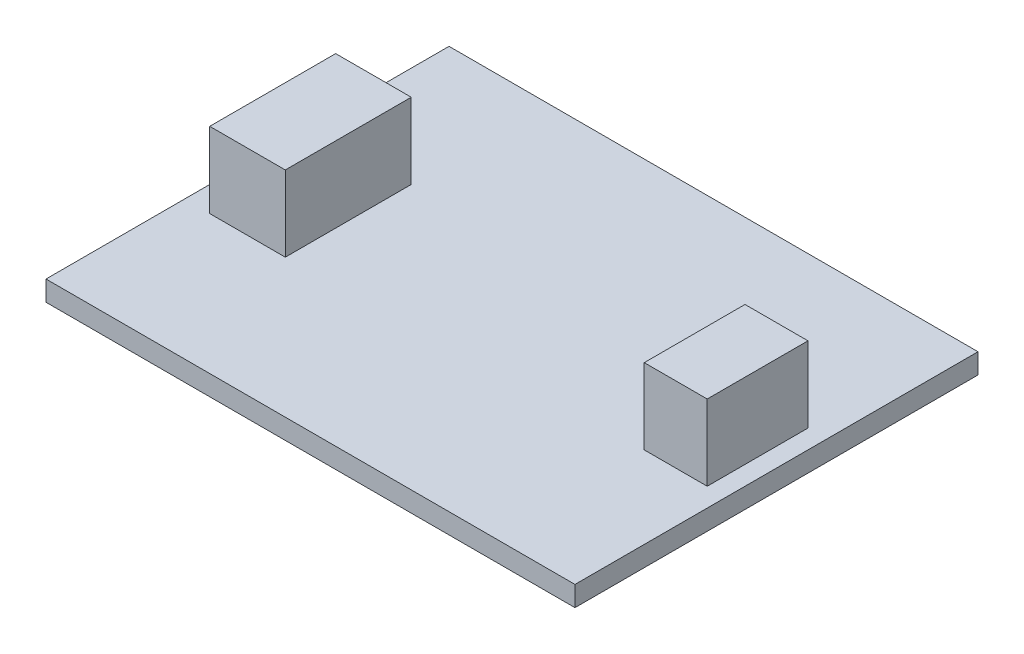
SolidWorks part; units mm, degrees
ref_plane "Front Plane" through (0, 0, 0) normal (0, 0, 1) x (1, 0, 0)
ref_plane "Top Plane" through (0, 0, 0) normal (0, 1, 0) x (1, 0, 0)
ref_plane "Right Plane" through (0, 0, 0) normal (1, 0, 0) x (0, 0, -1)
other "Configuration Table"
sketch "Sketch1" plane through (0, 0, 0) normal (0, 1, 0) x (1, 0, 0)
  line L1 (-21, -16) -> (21, -16)
  line L2 (-21, -16) -> (-21, 16)
  line L3 (-21, 16) -> (21, 16)
  line L4 (21, -16) -> (21, 16)
  line L5 (-21, -16) -> (21, 16) construction
  line L6 (-21, 16) -> (21, -16) construction
  point P6 (0, 0)
  dimension "D1" = 42
  dimension "D2" = 32
extrude "Board" add sketch "Sketch1" along normal blind 1.6
sketch "Sketch2" plane through (0, 0, 0) normal (0, 1, 0) x (1, 0, 0)
  line L0 (-19, -5) -> (-13, -5)
  line L1 (-13, -5) -> (-13, 5)
  line L2 (-13, 5) -> (-19, 5)
  line L3 (-19, 5) -> (-19, -5)
extrude "Probe_Connector" add sketch "Sketch2" along normal blind 6 from offset 1.6
sketch "Sketch3" plane through (0, 0, 0) normal (0, 1, 0) x (1, 0, 0)
  line L0 (14.5, -4) -> (19.5, -4)
  line L1 (19.5, -4) -> (19.5, 4)
  line L2 (19.5, 4) -> (14.5, 4)
  line L3 (14.5, 4) -> (14.5, -4)
extrude "Signal_Header" add sketch "Sketch3" along normal blind 6 from offset 1.6
equation "\"Jar_OD\"= 90  'ASSUMED - Part G fallback - jar outer diameter"
equation "\"Jar_H\"= 120  'ASSUMED - Part G fallback - jar height"
equation "\"Pump_L\"= 45  'ASSUMED - Part G fallback"
equation "\"Pump_W\"= 24  'ASSUMED - Part G fallback"
equation "\"Pump_H\"= 33  'ASSUMED - Part G fallback"
equation "\"Pump_Outlet_OD\"= 7.5  'ASSUMED - Part G fallback"
equation "\"Tube_OD\"= 8  'ASSUMED - Part G fallback"
equation "\"Tube_ID\"= 6  'ASSUMED - Part G fallback"
equation "\"TDS_Body_Dia\"= 12  'ASSUMED - Part G fallback"
equation "\"TDS_Wet_Len\"= 45  'ASSUMED - Part G fallback - length in water"
equation "\"DS_Tube_Dia\"= 6  'ASSUMED - Part G fallback"
equation "\"DS_Tube_Len\"= 50  'ASSUMED - Part G fallback"
equation "\"ORP_Body_Dia\"= 12  'ASSUMED - Part G fallback"
equation "\"ORP_Body_Len\"= 150  'ASSUMED - Part G fallback"
equation "\"ORP_Cap_Dia\"= 16  'ASSUMED - Part G fallback"
equation "\"Turb_W\"= 33  'ASSUMED - Part G fallback - head width"
equation "\"Turb_D\"= 28  'ASSUMED - Part G fallback - head depth"
equation "\"Turb_H\"= 30  'ASSUMED - Part G fallback - head height"
equation "\"Turb_Slot_W\"= 10  'ASSUMED - Part G fallback - slot width"
equation "\"Flow_L\"= 62  'ASSUMED - Part G fallback YF-S201"
equation "\"Flow_W\"= 36  'ASSUMED - Part G fallback"
equation "\"Flow_H\"= 35  'ASSUMED - Part G fallback"
equation "\"Thread_G12_OD\"= 20.955  'ASSUMED - Part G fallback thread G1/2 (major diameter)"
equation "\"Valve_L\"= 75  'ASSUMED - Part G fallback"
equation "\"Valve_W\"= 45  'ASSUMED - Part G fallback"
equation "\"Valve_H\"= 60  'ASSUMED - Part G fallback"
equation "\"Tee_L\"= 40  'ASSUMED - Part G fallback - overall length"
equation "\"Tee_Branch_L\"= 25  'ASSUMED - Part G fallback"
equation "\"Tee_OD\"= 12  'ASSUMED - Part G fallback"
equation "\"Cuv_W\"= 12.5  'ASSUMED - old R3 cuvette (station suppressed in SS4)"
equation "\"Cuv_D\"= 12.5  'ASSUMED - old R3 cuvette (station suppressed in SS4)"
equation "\"Cuv_H\"= 45  'ASSUMED - old R3 cuvette (station suppressed in SS4)"
equation "\"LED_Board_L\"= 20  'ASSUMED - Part G fallback"
equation "\"LED_Board_W\"= 20  'ASSUMED - Part G fallback - LED at centre"
equation "\"GUVA_L\"= 20  'ASSUMED - Part G fallback"
equation "\"GUVA_W\"= 12  'ASSUMED - Part G fallback - sensor at centre"
equation "\"Reed_L\"= 27  'ASSUMED - Part G fallback MC-38 half"
equation "\"Reed_W\"= 14  'ASSUMED - Part G fallback"
equation "\"Reed_H\"= 8  'ASSUMED - Part G fallback"
equation "\"ESP_L\"= 51  'ASSUMED - Part G fallback"
equation "\"ESP_W\"= 28  'ASSUMED - Part G fallback"
equation "\"TFT_L\"= 58  'ASSUMED - Part G fallback - board"
equation "\"TFT_W\"= 35  'ASSUMED - Part G fallback - board"
equation "\"TFT_Win_L\"= 35  'ASSUMED - Part G fallback - visible window"
equation "\"TFT_Win_W\"= 28  'ASSUMED - Part G fallback - visible window"
equation "\"Relay_L\"= 50  'ASSUMED - Part G fallback"
equation "\"Relay_W\"= 26  'ASSUMED - Part G fallback"
equation "\"Relay_H\"= 19  'ASSUMED - Part G fallback"
equation "\"Mosfet_L\"= 34  'ASSUMED - Part G fallback"
equation "\"Mosfet_W\"= 17  'ASSUMED - Part G fallback"
equation "\"Mosfet_H\"= 12  'ASSUMED - Part G fallback"
equation "\"TDS_Board_L\"= 42  'ASSUMED - Part G fallback"
equation "\"TDS_Board_W\"= 32  'ASSUMED - Part G fallback"
equation "\"Turb_Board_L\"= 38  'ASSUMED - Part G fallback"
equation "\"Turb_Board_W\"= 28  'ASSUMED - Part G fallback"
equation "\"BNC_Thread_Dia\"= 9.5  'ASSUMED - Part G fallback"
equation "\"Plate_L\"= 420  'ASSUMED - Part G fallback"
equation "\"Plate_W\"= 297  'ASSUMED - Part G fallback"
equation "\"Plate_T\"= 6  'ASSUMED - Part G fallback"
equation "\"Probe_Clr\"= 0.3  'DESIGN VALUE - Part C rule 3 - printed probe hole = diameter + 0.3"
equation "\"Cuv_Clr\"= 0.2  'DESIGN VALUE - Part C rule 3 - cuvette pocket = size + 0.2"
equation "\"Label_H\"= 0.6  'DESIGN VALUE - Part D - raised label height"
equation "\"D1@Sketch1\" = \"TDS_Board_L\""
equation "\"D2@Sketch1\" = \"TDS_Board_W\""
equation "\"Booster_L\"= 150  'ASSUMED - Part G fallback - booster pump"
equation "\"Booster_W\"= 95  'ASSUMED - Part G fallback"
equation "\"Booster_H\"= 100  'ASSUMED - Part G fallback"
equation "\"PTube_OD\"= 6.35  'ASSUMED - Part G fallback - product tube 1/4 inch"
equation "\"Qz_Out\"= 12  'ASSUMED - Part G fallback - quartz channel outside square"
equation "\"Qz_Path\"= 10  'ASSUMED - Part G fallback - quartz channel inside light path"
equation "\"Qz_L\"= 40  'ASSUMED - Part G fallback - quartz channel length"
equation "\"LED860_Dia\"= 5  'ASSUMED - Part G fallback - 860 nm LED"
equation "\"BPW_L\"= 5.4  'ASSUMED - Part G fallback - BPW34"
equation "\"BPW_W\"= 4.3  'ASSUMED - Part G fallback - BPW34"
equation "\"Cart_Dia\"= 50  'ASSUMED - Part G fallback - sediment and pre-carbon cartridges"
equation "\"Cart_L\"= 255  'ASSUMED - Part G fallback"
equation "\"UF_Dia\"= 50  'ASSUMED - Part G fallback - UF cartridge"
equation "\"UF_L\"= 260  'ASSUMED - Part G fallback"
equation "\"RO_Dia\"= 62  'ASSUMED - Part G fallback - RO membrane housing"
equation "\"RO_L\"= 300  'ASSUMED - Part G fallback"
equation "\"UVC_Dia\"= 40  'ASSUMED - Part G fallback - UV-C chamber"
equation "\"UVC_L\"= 300  'ASSUMED - Part G fallback"
equation "\"Tank_W\"= 260  'ASSUMED - Part G fallback - storage tank"
equation "\"Tank_D\"= 160  'ASSUMED - Part G fallback"
equation "\"Tank_H\"= 300  'ASSUMED - Part G fallback"
equation "\"Cab_W\"= 400  'ASSUMED - Part G fallback - purifier cabinet"
equation "\"Cab_D\"= 270  'ASSUMED - Part G fallback"
equation "\"Cab_H\"= 560  'ASSUMED - Part G fallback"
equation "\"ORP_Board_L\"= 40  'ASSUMED - Part G fallback - ORP buffer board"
equation "\"ORP_Board_W\"= 30  'ASSUMED - Part G fallback"
equation "\"Opt_Board_L\"= 50  'ASSUMED - Part G fallback - optical front-end board"
equation "\"Opt_Board_W\"= 40  'ASSUMED - Part G fallback"
equation "\"Buck_L\"= 43  'ASSUMED - Part G fallback - 12 V to 5 V buck module"
equation "\"Buck_W\"= 21  'ASSUMED - Part G fallback"
equation "\"Buck_H\"= 14  'ASSUMED - Part G fallback"
equation "\"BB_L\"= 165  'ASSUMED - Part G fallback - breadboard (As_Built_R3 only)"
equation "\"BB_W\"= 55  'ASSUMED - Part G fallback"
equation "\"BB_H\"= 10  'ASSUMED - Part G fallback"
